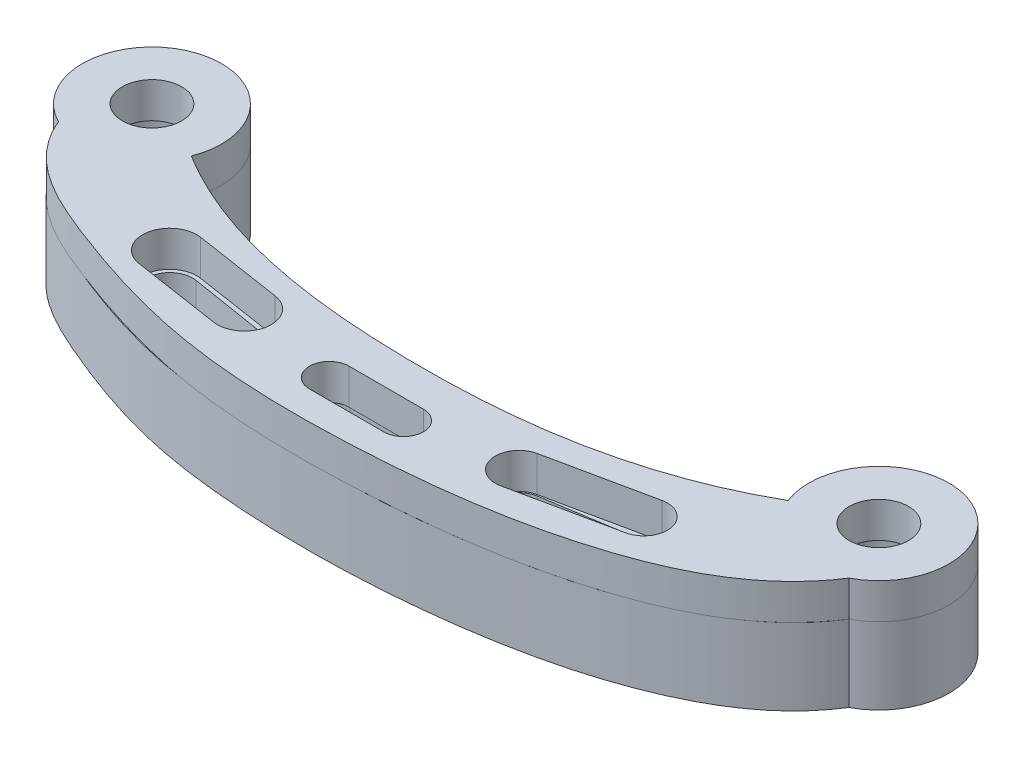
SolidWorks part; units mm, degrees
ref_plane "Front Plane" through (0, 0, 0) normal (0, 0, 1) x (1, 0, 0)
ref_plane "Top Plane" through (0, 0, 0) normal (0, 1, 0) x (1, 0, 0)
ref_plane "Right Plane" through (0, 0, 0) normal (1, 0, 0) x (0, 0, -1)
sketch "Sketch1" plane through (0, 0, 0) normal (0, 1, 0) x (1, 0, 0)
  line L0 (163.9337, 69.6332) -> (225.635, 59.6067) construction
  line L1 (166.3499, 84.502) -> (228.0512, 74.4755)
  line L2 (161.5175, 54.7644) -> (223.2188, 44.7379)
  line L3 (288.1076, 49.7512) -> (336.6973, 49.7512) construction
  line L4 (288.1076, 63.4631) -> (336.6973, 63.4631)
  line L5 (288.1076, 36.0393) -> (336.6973, 36.0393)
  line L6 (402.255, 59.6067) -> (465.4988, 69.6332) construction
  line L7 (399.9843, 73.929) -> (463.2282, 83.9555)
  line L8 (404.5256, 45.2844) -> (467.7694, 55.3109)
  circle A0 centre (75.2381, 146.7598) radius 23.9146
  circle A1 centre (550.3381, 146.7598) radius 27.046
  arc A2 (571.4256, 106.091) -> (507.6594, 130.1114) centre (550.3381, 146.7598) ccw
  arc A3 (117.616, 130.1114) -> (54.766, 106.091) centre (75.2381, 146.7598) ccw
  arc A4 (166.3499, 84.502) -> (161.5175, 54.7644) centre (163.9337, 69.6332) ccw
  arc A5 (223.2188, 44.7379) -> (228.0512, 74.4755) centre (225.635, 59.6067) ccw
  arc A6 (288.1076, 63.4631) -> (288.1076, 36.0393) centre (288.1076, 49.7512) ccw
  arc A7 (336.6973, 36.0393) -> (336.6973, 63.4631) centre (336.6973, 49.7512) ccw
  arc A8 (399.9843, 73.929) -> (404.5256, 45.2844) centre (402.255, 59.6067) ccw
  arc A9 (467.7694, 55.3109) -> (463.2282, 83.9555) centre (465.4988, 69.6332) ccw
  spline S0 degree 3 poles (117.616, 130.1114) (144.2042, 106.4572) (190.1406, 101.8644) (251.0312, 86.2153) (297.388, 86.1319) (353.7073, 84.1675) (425.3057, 96.1772) (479.0495, 111.5351) (507.6594, 130.1114) knots 0 0 0 0 0.24967 0.333275 0.464807 0.590409 0.750006 1 1 1 1
  spline S1 degree 3 poles (571.4256, 106.091) (553.6968, 77.5313) (499.7916, 45.7599) (413.1752, 24.948) (335.7951, 17.7024) (264.3414, 18.4722) (192.347, 26.1409) (119.36, 51.3079) (64.7626, 78.8736) (54.766, 106.091) knots 0 0 0 0 0.174459 0.318402 0.471929 0.585168 0.697863 0.852812 1 1 1 1
  point P20 (194.7844, 64.62)
  point P31 (312.4024, 49.7512)
  point P39 (433.8769, 64.62)
extrude "Boss-Extrude1" add sketch "Sketch1" along normal blind 50
scale "Scale1" scale about origin uniform scaling yes scale factor 0.129
sketch "Sketch2" plane through (0, 6.45, 0) normal (0, 1, 0) x (1, 0, 0)
  line L0 (21.1474, 8.9827) -> (28.5814, 7.8451) construction
  line L1 (21.4924, 11.2372) -> (28.9263, 10.0996)
  line L2 (20.8025, 6.7282) -> (28.2364, 5.5906)
  line L3 (37.1659, 6.4179) -> (43.434, 6.4179) construction
  line L4 (37.1659, 8.0842) -> (43.434, 8.0842)
  line L5 (37.1659, 4.7516) -> (43.434, 4.7516)
  line L6 (51.8909, 7.6893) -> (60.5777, 9.5234) construction
  line L7 (51.479, 9.6402) -> (60.1657, 11.4744)
  line L8 (52.3028, 5.7383) -> (60.9896, 7.5725)
  circle A0 centre (9.7057, 18.932) radius 2.5
  circle A1 centre (70.9936, 18.932) radius 2.5
  arc A2 (15.1725, 16.7844) -> (7.0648, 13.6857) centre (9.7057, 18.932) ccw
  arc A3 (73.7139, 13.6857) -> (65.4881, 16.7844) centre (70.9936, 18.932) ccw
  arc A4 (21.4924, 11.2372) -> (20.8025, 6.7282) centre (21.1474, 8.9827) ccw
  arc A5 (28.2364, 5.5906) -> (28.9263, 10.0996) centre (28.5814, 7.8451) ccw
  arc A6 (37.1659, 8.0842) -> (37.1659, 4.7516) centre (37.1659, 6.4179) ccw
  arc A7 (43.434, 4.7516) -> (43.434, 8.0842) centre (43.434, 6.4179) ccw
  arc A8 (51.479, 9.6402) -> (52.3028, 5.7383) centre (51.8909, 7.6893) ccw
  arc A9 (60.9896, 7.5725) -> (60.1657, 11.4744) centre (60.5777, 9.5234) ccw
  spline S0 degree 3 poles (15.1725, 16.7844) (22.1776, 12.4423) (39.7491, 9.8544) (57.1826, 12.0575) (65.4881, 16.7844) knots 0 0 0 0 0.465546 1 1 1 1
  spline S1 degree 3 poles (65.4881, 16.7844) (61.7974, 14.388) (54.8644, 12.4069) (45.6282, 10.8576) (38.3631, 11.111) (32.383, 11.1218) (24.5281, 13.1405) (18.6023, 13.733) (15.1725, 16.7844) knots 0 0 0 0 0.249994 0.409591 0.535193 0.666725 0.75033 1 1 1 1 construction
  spline S2 degree 3 poles (7.0648, 13.6857) (8.6996, 9.7125) (16.3001, 6.2515) (29.0249, 2.261) (44.2577, 2.1268) (60.4206, 4.1812) (70.7433, 9.0572) (73.7139, 13.6857) knots 0 0 0 0 0.164036 0.328595 0.550971 0.781411 1 1 1 1
  spline S3 degree 3 poles (7.0648, 13.6857) (8.3544, 10.1747) (15.3974, 6.6187) (24.8128, 3.3722) (34.1, 2.3829) (43.3176, 2.2836) (53.2996, 3.2183) (64.4731, 5.903) (71.4269, 10.0015) (73.7139, 13.6857) knots 0 0 0 0 0.147188 0.302137 0.414832 0.528071 0.681598 0.825541 1 1 1 1 construction
  point P14 (24.8644, 8.4139)
  point P29 (40.2999, 6.4179)
  point P44 (56.2343, 8.6064)
extrude "Boss-Extrude2" add sketch "Sketch2" along normal blind 3 separate body
